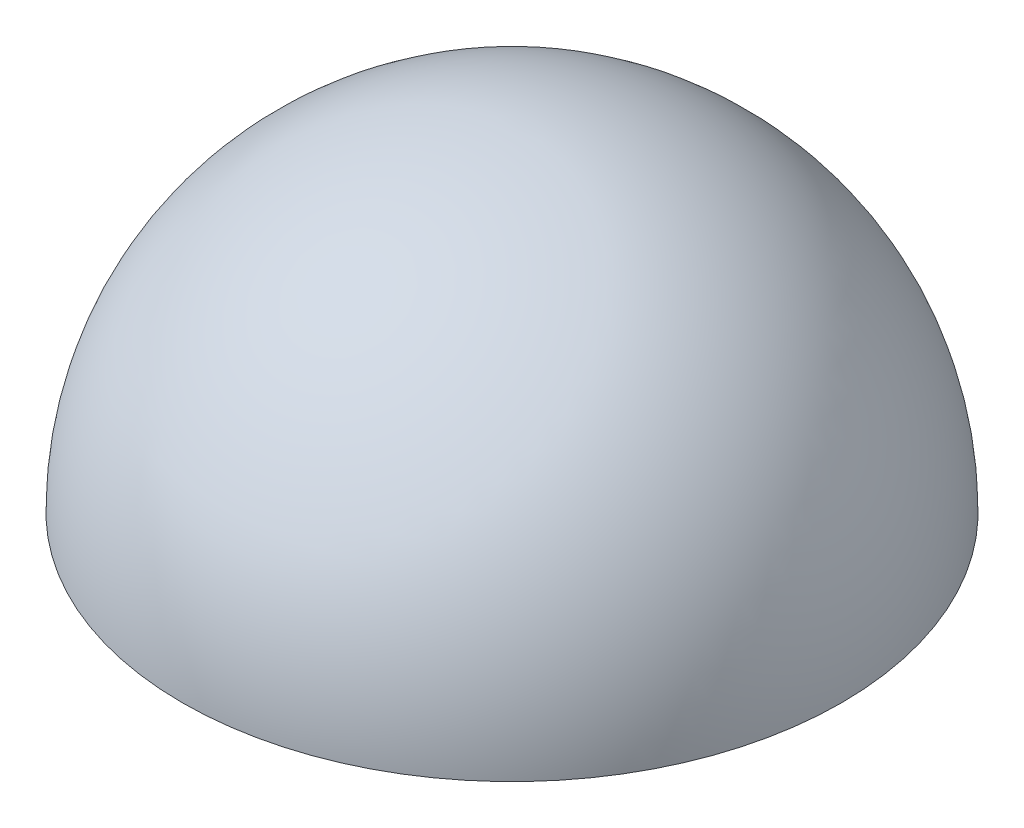
SolidWorks part; units mm, degrees
ref_plane "Front Plane" through (0, 0, 0) normal (0, 0, 1) x (1, 0, 0)
ref_plane "Top Plane" through (0, 0, 0) normal (0, 1, 0) x (1, 0, 0)
ref_plane "Right Plane" through (0, 0, 0) normal (1, 0, 0) x (0, 0, -1)
sketch "Sketch1" plane through (0, 0, 0) normal (0, 1, 0) x (1, 0, 0)
  circle A0 centre (0, 0) radius 12.4
  dimension "D1" = 24.8
extrude "Boss-Extrude1" add sketch "Sketch1" along normal blind 5
ref_axis "Axis1" through (0, 42.9262, 0) along (0, -1, 0)
sketch "Sketch2" plane through (0, 0, 0) normal (0, 0, 1) x (1, 0, 0)
  line L0 (0, 5) -> (0, 55)
  line L1 (12.4, 5) -> (-12.4, 5) construction
  line L2 (0, 42.9262) -> (0, -13.0646) construction
  line L3 (0, 5) -> (50, 5)
  arc A0 (50, 5) -> (0, 55) centre (0, 5) ccw
  dimension "D1" = 50
revolve "Revolve1" add sketch "Sketch2" angle 360 about axis through (0, 42.9262, 0) along (0, -1, 0)
